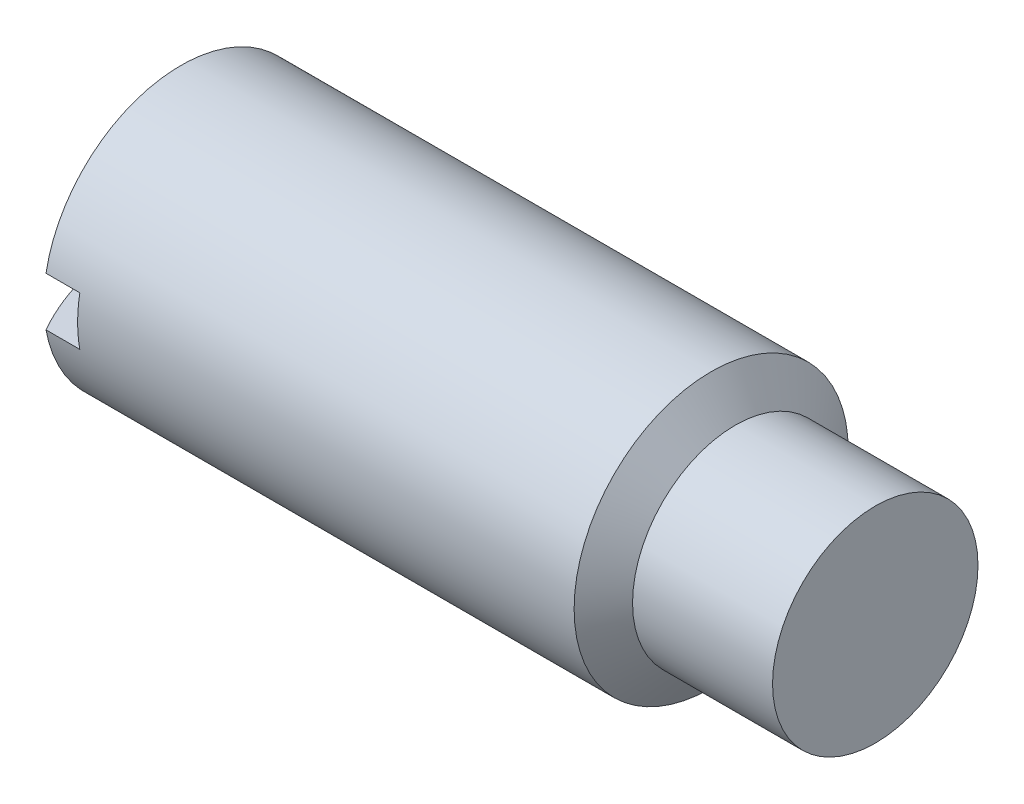
SolidWorks part; units mm, degrees
revolve "BaseBody" add sketch "BodySke" angle 360 about L5
sketch "BodySke" plane through (0, 0, 0) normal (0, 0, 1) x (1, 0, 0)
  line L0 (2.5522, -9.525) -> (19.05, -9.525) construction
  line L1 (41.0718, 7.1374) -> (50.8, 7.1374)
  line L2 (2.5522, 9.525) -> (39.4, 9.525)
  line L3 (41.0718, 7.1374) -> (39.4, 9.525)
  line L4 (50.8, 0) -> (0, 0)
  line L5 (-12.7, 0) -> (88.9, 0) construction
  line L6 (2.0066, 12.7) -> (2.0066, -6.35) construction
  line L7 (50.8, 7.1374) -> (50.8, 0)
  line L8 (41.0718, -7.1374) -> (50.8, -7.1374) construction
  arc A1 (2.5522, 9.525) -> (0, 0) centre (19.05, 0) ccw
  dimension "Crown_radius" = 19.05
  dimension "Diameter" = 19.05
  dimension "Dog_dia" = 14.2748
  dimension "D1" = 125
  dimension "Length" = 50.8
  dimension "Dog_len" = 9.7282
  dimension "Advance" = 2.0066
cosmetic thread "ThreadCosmetic" [suppressed] parameters "Thread_minor"=16.0249
extrude "Slot" cut sketch "Sketch2" along normal blind 4.9022
sketch "Sketch2" plane through (0, 0, 0) normal (1, 0, 0) x (0, 0, -1)
  line L1 (9.525, -1.7018) -> (-9.525, -1.7018)
  line L2 (9.525, -1.7018) -> (9.525, 1.7018)
  line L3 (9.525, 1.7018) -> (-9.525, 1.7018)
  line L4 (-9.525, -1.7018) -> (-9.525, 1.7018)
  dimension "D1" = 19.05
  dimension "Slot_width" = 3.4036
  dimension "D3" = 9.525
  dimension "D2" = 1.7018
ref_plane "Plane1" through (0, 0, 0) normal (0, 0, 1) x (1, 0, 0)
ref_plane "Plane2" through (0, 0, 0) normal (0, 1, 0) x (1, 0, 0)
ref_plane "Plane3" through (0, 0, 0) normal (1, 0, 0) x (0, 0, -1)
sketch "ThdSchSke" plane through (0, 0, 0) normal (0, 0, 1) x (1, 0, 0)
  line L0 (2.5522, -8.0124) -> (1.4931, -9.525)
  line L1 (2.5522, -8.0124) -> (3.6113, -9.525)
  line L2 (3.6113, -9.525) -> (3.6113, -11.9063)
  line L3 (-3.175, 0) -> (5.1513, 0) construction
  line L4 (2.5522, -9.525) -> (2.5522, -1.7018) construction
  line L5 (3.6113, -11.9063) -> (1.4931, -11.9063)
  line L6 (1.4931, -11.9063) -> (1.4931, -9.525)
  dimension "Diameter" = 19.05
  dimension "Thread_minor" = 16.0249
revolve "ThreadSchematic" [suppressed] cut sketch "ThdSchSke" angle 360 about L3
pattern_linear "ThdSchPat" [suppressed]
equation "\"D1@Sketch2\" = \"Diameter@BodySke\""
equation "\"D3@Sketch2\" = \"D1@Sketch2\" / 2"
equation "\"D2@Sketch2\" = \"Slot_width@Sketch2\" / 2"
equation "\"Thread_minor@ThdSchSke\" = \"Thread_minor@ThreadCosmetic\""
equation "\"Diameter@ThdSchSke\" = \"Diameter@BodySke\""
equation "\"Overcut@ThdSchSke\" = \"Diameter@BodySke\" * 1.25"
equation "\"Num_threads@ThdSchPat\" = int ( ( \"Length@BodySke\" - ( \"Crown_radius@BodySke\" - sqr ( ( \"Crown_radius@BodySke\" * \"Crown_radius@BodySke\" ) - ( ( \"Diameter@BodySke\" * 0.5 ) * ( \"Diameter@BodySke\" * 0.5 ) ) ) ) - \"Dog_len@BodySke\" ) / \"Advance@BodySke\" + 0.999 )  + 1"
equation "\"Advance@ThdSchPat\" = ( \"Length@BodySke\" - ( \"Crown_radius@BodySke\" - sqr ( ( \"Crown_radius@BodySke\" * \"Crown_radius@BodySke\" ) - ( ( \"Diameter@BodySke\" * 0.5 ) * ( \"Diameter@BodySke\" * 0.5 ) ) ) ) - \"Dog_len@BodySke\" ) /  (\"Num_threads@ThdSchPat\" - 1) 'relax it"
equation "\"Num_threads@ThdSchPat\" = \"Num_threads@ThdSchPat\" - sgn( \"Num_threads@ThdSchPat\" - 1) '---chamfered tips only---"
